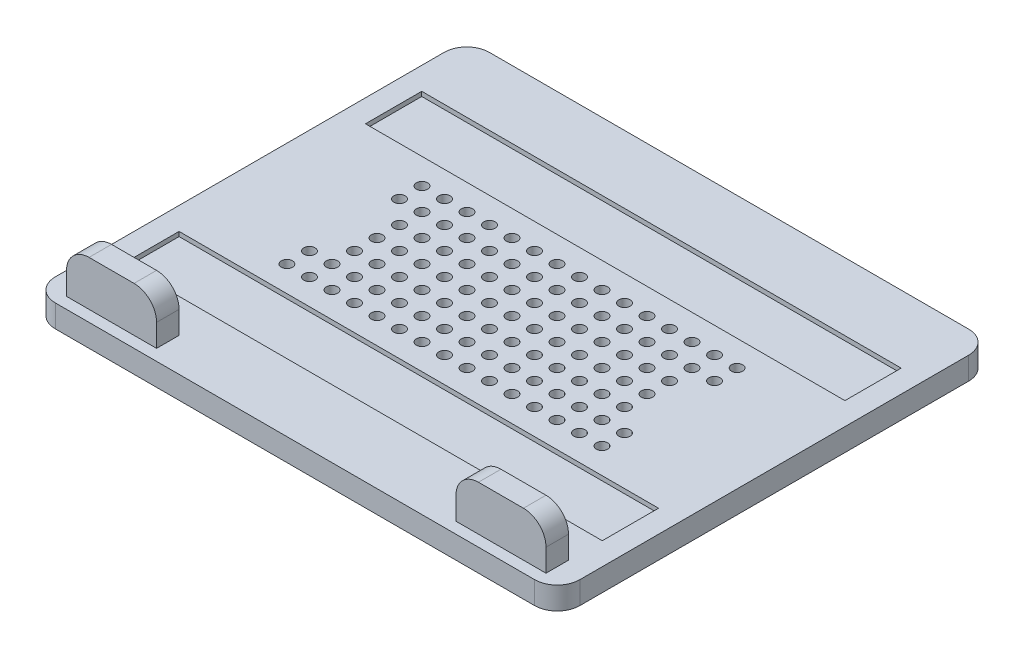
SolidWorks part; units mm, degrees
material "Oak"
ref_plane "Front Plane" through (0, 0, 0) normal (0, 0, 1) x (1, 0, 0)
ref_plane "Top Plane" through (0, 0, 0) normal (0, 1, 0) x (1, 0, 0)
ref_plane "Right Plane" through (0, 0, 0) normal (1, 0, 0) x (0, 0, -1)
sketch "Sketch1" plane through (0, 0, 0) normal (0, 1, 0) x (1, 0, 0)
  line L1 (-147.955, 122.428) -> (147.955, 122.428)
  line L2 (-147.955, 122.428) -> (-147.955, -122.428)
  line L3 (-147.955, -122.428) -> (147.955, -122.428)
  line L4 (147.955, 122.428) -> (147.955, -122.428)
  line L5 (-147.955, 122.428) -> (147.955, -122.428) construction
  line L6 (-147.955, -122.428) -> (147.955, 122.428) construction
  point P0 (0, 0)
  dimension "D1" = 295.91
  dimension "D2" = 244.856
extrude "Boss-Extrude1" add sketch "Sketch1" along normal blind 12.7
sketch "Sketch2" plane through (0, 12.7, 0) normal (0, 1, 0) x (1, 0, 0)
  line L0 (147.955, 122.428) -> (-147.955, 122.428) construction
  line L1 (147.955, -122.428) -> (147.955, 122.428) construction
  circle A0 centre (0, 0) radius 3.175
  circle A1 centre (12.7, 0) radius 3.175
  circle A2 centre (25.4, 0) radius 3.175
  circle A3 centre (38.1, 0) radius 3.175
  circle A4 centre (50.8, 0) radius 3.175
  circle A5 centre (63.5, 0) radius 3.175
  circle A6 centre (76.2, 0) radius 3.175
  circle A8 centre (12.7, 12.7) radius 3.175
  circle A9 centre (25.4, 12.7) radius 3.175
  circle A10 centre (38.1, 12.7) radius 3.175
  circle A11 centre (50.8, 12.7) radius 3.175
  circle A12 centre (63.5, 12.7) radius 3.175
  circle A13 centre (76.2, 12.7) radius 3.175
  circle A15 centre (12.7, 25.4) radius 3.175
  circle A16 centre (25.4, 25.4) radius 3.175
  circle A17 centre (38.1, 25.4) radius 3.175
  circle A18 centre (50.8, 25.4) radius 3.175
  circle A19 centre (63.5, 25.4) radius 3.175
  circle A20 centre (76.2, 25.4) radius 3.175
  circle A21 centre (88.9, 25.4) radius 3.175
  circle A22 centre (12.7, 38.1) radius 3.175
  circle A23 centre (25.4, 38.1) radius 3.175
  circle A24 centre (38.1, 38.1) radius 3.175
  circle A25 centre (50.8, 38.1) radius 3.175
  circle A26 centre (63.5, 38.1) radius 3.175
  circle A27 centre (76.2, 38.1) radius 3.175
  circle A28 centre (88.9, 38.1) radius 3.175
  circle A29 centre (0, 12.7) radius 3.175
  circle A30 centre (0, 25.4) radius 3.175
  circle A31 centre (0, 38.1) radius 3.175
  circle A32 centre (88.9, 0) radius 3.175 [skipped]
  circle A33 centre (88.9, 12.7) radius 3.175 [skipped]
  dimension "D1" = 6.35
  dimension "D4" = 84.328
  dimension "D5" = 59.055
  dimension "D2" = 8
  dimension "D3" = 4
extrude "Cut-Extrude1" cut sketch "Sketch2" against normal through all
mirror "Mirror5" about plane through (0, 0, 0) normal (0, 0, 1) of "Cut-Extrude1"
mirror "Mirror6" about plane through (0, 0, 0) normal (1, 0, 0) of "Mirror5", "Cut-Extrude1"
sketch "Sketch3" plane through (0, 12.7, 0) normal (0, 1, 0) x (1, 0, 0)
  line L0 (-147.955, -122.428) -> (147.955, -122.428) construction
  line L1 (-135.255, -103.378) -> (-84.455, -103.378)
  line L2 (-135.255, -103.378) -> (-135.255, -116.078)
  line L3 (-135.255, -116.078) -> (-84.455, -116.078)
  line L4 (-84.455, -103.378) -> (-84.455, -116.078)
  line L5 (-135.255, -103.378) -> (-84.455, -116.078) construction
  line L6 (-135.255, -116.078) -> (-84.455, -103.378) construction
  line L7 (-147.955, 122.428) -> (-147.955, -122.428) construction
  point P0 (-109.855, -109.728)
  dimension "D1" = 12.7
  dimension "D2" = 12.7
  dimension "D3" = 50.8
  dimension "D4" = 12.7
extrude "Boss-Extrude2" add sketch "Sketch3" along normal blind 25.4
fillet "Fillet1" radius 12.7 2 edges at (-84.455, 38.1, 109.728) (-135.255, 38.1, 109.728)
mirror "Mirror7" about plane through (0, 0, 0) normal (1, 0, 0) of "Boss-Extrude2", "Fillet1"
fillet "Fillet2" radius 12.7 4 edges at (-147.955, 6.35, 122.428) (-147.955, 6.35, -122.428) (147.955, 6.35, -122.428) (147.955, 6.35, 122.428)
sketch "Sketch4" plane through (0, 12.7, 0) normal (0, 1, 0) x (1, 0, 0)
  line L1 (-135.255, 84.328) -> (135.255, 84.328)
  line L2 (-135.255, 84.328) -> (-135.255, 52.578)
  line L3 (-135.255, 52.578) -> (135.255, 52.578)
  line L4 (135.255, 84.328) -> (135.255, 52.578)
  line L5 (-135.255, 84.328) -> (135.255, 52.578) construction
  line L6 (-135.255, 52.578) -> (135.255, 84.328) construction
  line L7 (-147.955, 109.728) -> (-147.955, -109.728) construction
  line L8 (147.955, -109.728) -> (147.955, 109.728) construction
  line L9 (135.255, 122.428) -> (-135.255, 122.428) construction
  line L10 (-6.985, 0) -> (6.985, 0) construction
  line L11 (-135.255, -52.578) -> (135.255, -52.578)
  line L12 (135.255, -84.328) -> (135.255, -52.578)
  line L13 (-135.255, -84.328) -> (135.255, -84.328)
  line L14 (-135.255, -84.328) -> (-135.255, -52.578)
  point P0 (0, 68.453)
  dimension "D1" = 31.75
  dimension "D2" = 12.7
  dimension "D3" = 38.1
  dimension "0.5" = 12.7
extrude "Cut-Extrude2" cut sketch "Sketch4" against normal blind 2.54
sketch "Sketch5" plane through (0, 0, 0) normal (0, -1, 0) x (1, 0, 0)
  line L0 (-1000, 0) -> (49000, 0) construction
  line L2 (-115.5319, 12.7) -> (-102.8319, 12.7)
  line L3 (-115.5319, 12.7) -> (-115.5319, -12.7)
  line L4 (-115.5319, -12.7) -> (-102.8319, -12.7)
  line L5 (-102.8319, 12.7) -> (-102.8319, -12.7)
  line L6 (-115.5319, 12.7) -> (-102.8319, -12.7) construction
  line L7 (-115.5319, -12.7) -> (-102.8319, 12.7) construction
  line L9 (-147.955, -109.728) -> (-147.955, 109.728) construction
  point P1 (-109.1819, 0)
  dimension "D1" = 12.7
  dimension "D2" = 25.4
  dimension "D3" = 32.4231
extrude "Boss-Extrude3" add sketch "Sketch5" along normal blind 19.05
sketch "Sketch6" plane through (-115.5319, 0, 0) normal (-1, 0, 0) x (0, 0, 1)
  line L0 (-12.7, -19.05) -> (12.7, -19.05)
  arc A0 (12.7, -19.05) -> (-12.7, -19.05) centre (0, -19.05) cw
  dimension "D1" = 12.7
extrude "Boss-Extrude4" add sketch "Sketch6" against normal up to surface (12.7 mm away) up to face at (-102.8319, -9.525, 0)
mirror "Mirror10" about plane through (0, 0, 0) normal (1, 0, 0) of "Boss-Extrude4", "Boss-Extrude3"
sketch "Sketch8" plane through (115.5319, 0, 0) normal (1, 0, 0) x (0, 0, -1)
  line L0 (0, 0) -> (0, -17.78) construction
  circle A0 centre (0, -17.78) radius 6.35
  arc A1 (-12.7, -19.05) -> (12.7, -19.05) centre (0, -19.05) ccw construction
  point P6 (0, -31.75)
  dimension "D1" = 12.7
  dimension "D2" = 17.78
extrude "Cut-Extrude3" cut sketch "Sketch8" against normal up to surface (231.0638 mm away) up to face at (-115.5319, -12.7, 0)
